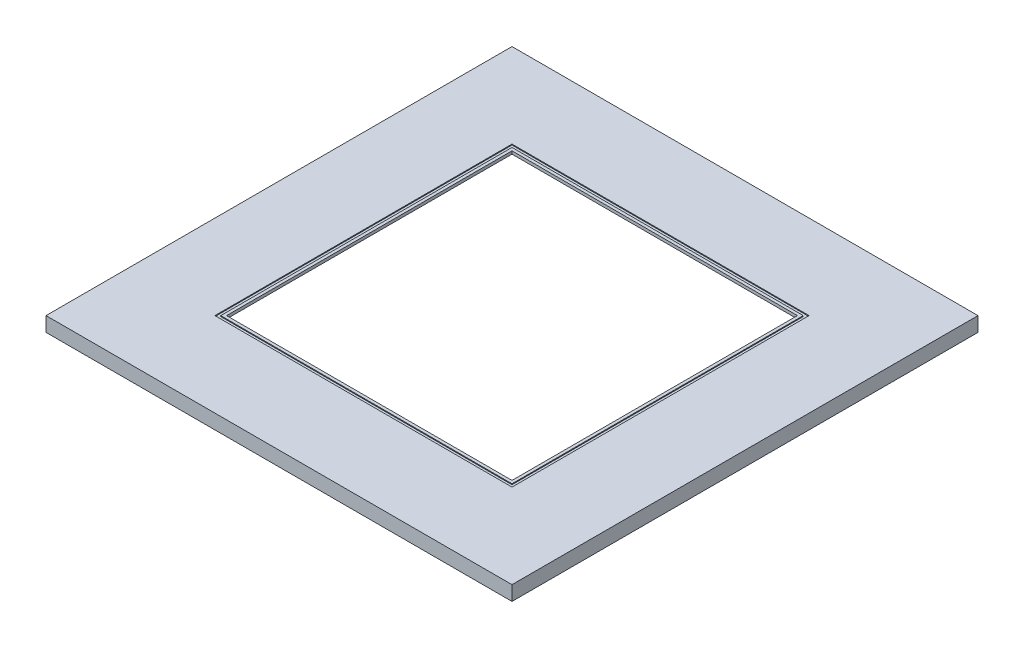
SolidWorks part; units mm, degrees
ref_plane "Alzado" through (0, 0, 0) normal (0, 0, 1) x (1, 0, 0)
ref_plane "Planta" through (0, 0, 0) normal (0, 1, 0) x (1, 0, 0)
ref_plane "Vista lateral" through (0, 0, 0) normal (1, 0, 0) x (0, 0, -1)
sketch "Croquis1" plane through (0, 0, 0) normal (0, 1, 0) x (1, 0, 0)
  line L0 (-5, -5) -> (-5, 155)
  line L1 (0, 0) -> (150, 0)
  line L2 (0, 0) -> (0, 150)
  line L3 (0, 150) -> (150, 150)
  line L4 (150, 0) -> (150, 150)
  line L5 (-5, 155) -> (155, 155)
  line L6 (155, -5) -> (155, 155)
  line L7 (-5, -5) -> (155, -5)
  dimension "D1" = 150
  dimension "D2" = 5
extrude "Saliente-Extruir1" add sketch "Croquis1" along normal blind 5
sketch "Croquis2" plane through (0, 5, 0) normal (0, 1, 0) x (1, 0, 0)
  line L0 (0, 0) -> (150, 0) construction
  line L1 (150, 0) -> (150, 150) construction
  line L2 (150, 150) -> (0, 150) construction
  line L3 (0, 150) -> (0, 0) construction
  line L4 (0, 0) -> (150, 0)
  line L5 (150, 0) -> (150, 150)
  line L6 (150, 150) -> (0, 150)
  line L7 (0, 150) -> (0, 0)
  line L8 (26, 26) -> (124, 26)
  line L9 (124, 26) -> (124, 124)
  line L10 (124, 124) -> (26, 124)
  line L11 (26, 124) -> (26, 26)
  dimension "D1" = 26
extrude "Saliente-Extruir2" add sketch "Croquis2" against normal blind 1
sketch "Croquis3" plane through (0, 5, 0) normal (0, 1, 0) x (1, 0, 0)
  line L4 (24, 24) -> (126, 24)
  line L5 (126, 24) -> (126, 126)
  line L6 (126, 126) -> (24, 126)
  line L7 (24, 126) -> (24, 24)
  line L8 (25, 25) -> (125, 25)
  line L9 (125, 25) -> (125, 125)
  line L10 (125, 125) -> (25, 125)
  line L11 (25, 125) -> (25, 25)
  line L12 (25, 25) -> (125, 25)
  line L13 (125, 25) -> (125, 125)
  line L14 (125, 125) -> (25, 125)
  line L15 (25, 125) -> (25, 25)
  dimension "D1" = 1
  dimension "D2" = 1
extrude "Cortar-Extruir1" cut sketch "Croquis3" against normal blind 0.3
